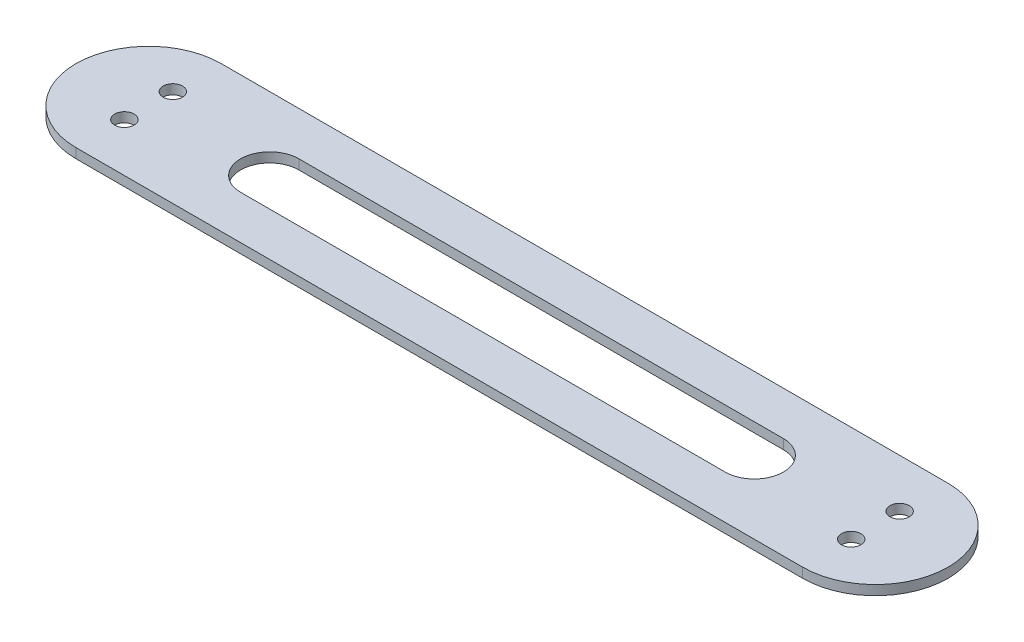
SolidWorks part; units mm, degrees
ref_plane "前视基准面" through (0, 0, 0) normal (0, 0, 1) x (1, 0, 0)
ref_plane "上视基准面" through (0, 0, 0) normal (0, 1, 0) x (1, 0, 0)
ref_plane "右视基准面" through (0, 0, 0) normal (1, 0, 0) x (0, 0, -1)
other "Configuration Table"
sketch "草图1" plane through (0, 0, 0) normal (0, 1, 0) x (1, 0, 0)
  line L0 (-75, 0) -> (75, 0) construction
  line L1 (-75, 15) -> (75, 15)
  line L2 (-75, -15) -> (75, -15)
  arc A0 (-75, 15) -> (-75, -15) centre (-75, 0) ccw
  arc A1 (75, -15) -> (75, 15) centre (75, 0) ccw
  point P2 (0, 0)
  dimension "D1" = 150
  dimension "D2" = 30
extrude "凸台-拉伸1" add sketch "草图1" along normal blind 2
sketch "草图2" plane through (0, 2, 0) normal (0, 1, 0) x (1, 0, 0)
  line L0 (-95.4858, 0) -> (96.883, 0) construction
  line L1 (0, 18.4326) -> (0, -20.2803) construction
  line L2 (-50, 0) -> (50, 0) construction
  line L3 (-50, 6) -> (50, 6)
  line L4 (-50, -6) -> (50, -6)
  circle A0 centre (-75, 5) radius 2
  circle A1 centre (-75, -5) radius 2
  circle A2 centre (75, -5) radius 2
  circle A3 centre (75, 5) radius 2
  arc A4 (-50, 6) -> (-50, -6) centre (-50, 0) ccw
  arc A5 (50, -6) -> (50, 6) centre (50, 0) ccw
  point P15 (0, 0)
  point P20 (-75.2508, -5)
  dimension "D1" = 4
  dimension "D2" = 5
  dimension "D3" = 100
  dimension "D4" = 12
extrude "切除-拉伸1" cut sketch "草图2" against normal blind 2
